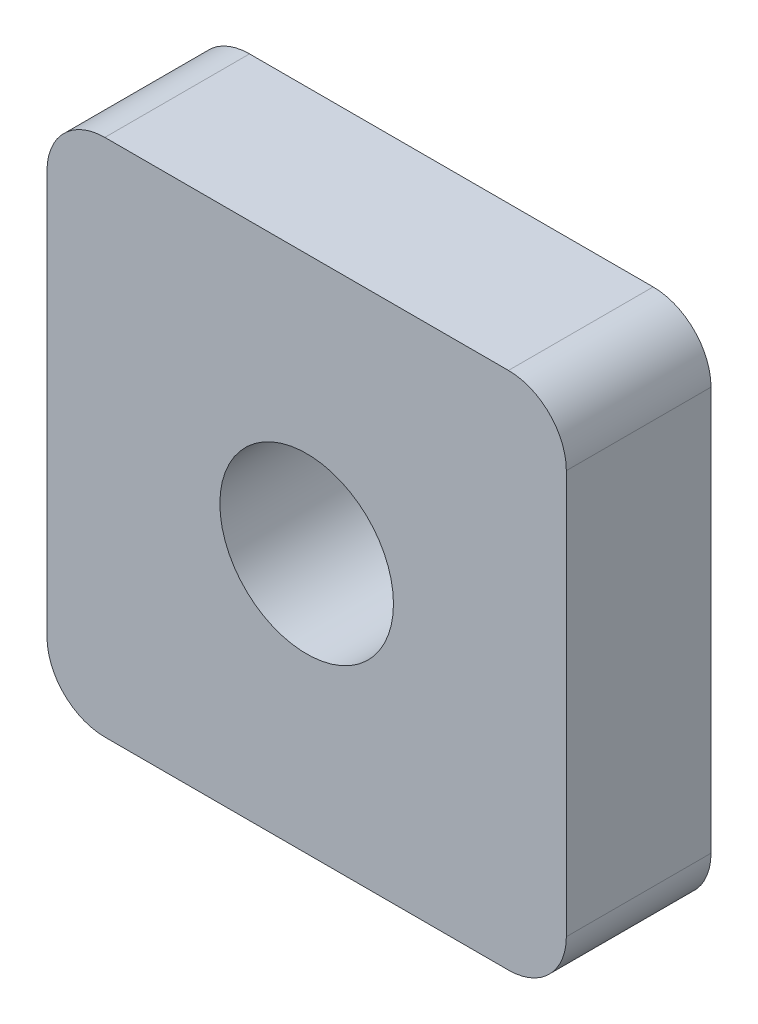
SolidWorks part; units mm, degrees
material "Thornel Mat VMA"
ref_plane "前视基准面" through (0, 0, 0) normal (0, 0, 1) x (1, 0, 0)
ref_plane "上视基准面" through (0, 0, 0) normal (0, 1, 0) x (1, 0, 0)
ref_plane "右视基准面" through (0, 0, 0) normal (1, 0, 0) x (0, 0, -1)
other "Configuration Table"
sketch "草图1" plane through (0, 0, 0) normal (0, 0, 1) x (1, 0, 0)
  line L1 (-8.975, -8.975) -> (8.975, -8.975)
  line L2 (-8.975, -8.975) -> (-8.975, 8.975)
  line L3 (-8.975, 8.975) -> (8.975, 8.975)
  line L4 (8.975, -8.975) -> (8.975, 8.975)
  line L5 (-8.975, -8.975) -> (8.975, 8.975) construction
  line L6 (-8.975, 8.975) -> (8.975, -8.975) construction
  circle A0 centre (0, 0) radius 3
  point P0 (0, 0)
  dimension "D1" = 6
  dimension "D2" = 17.95
extrude "凸台-拉伸1" add sketch "草图1" along normal blind 5
fillet "圆角1" radius 2 4 edges at (8.975, -8.975, 2.5) (-8.975, -8.975, 2.5) (-8.975, 8.975, 2.5) (8.975, 8.975, 2.5)
